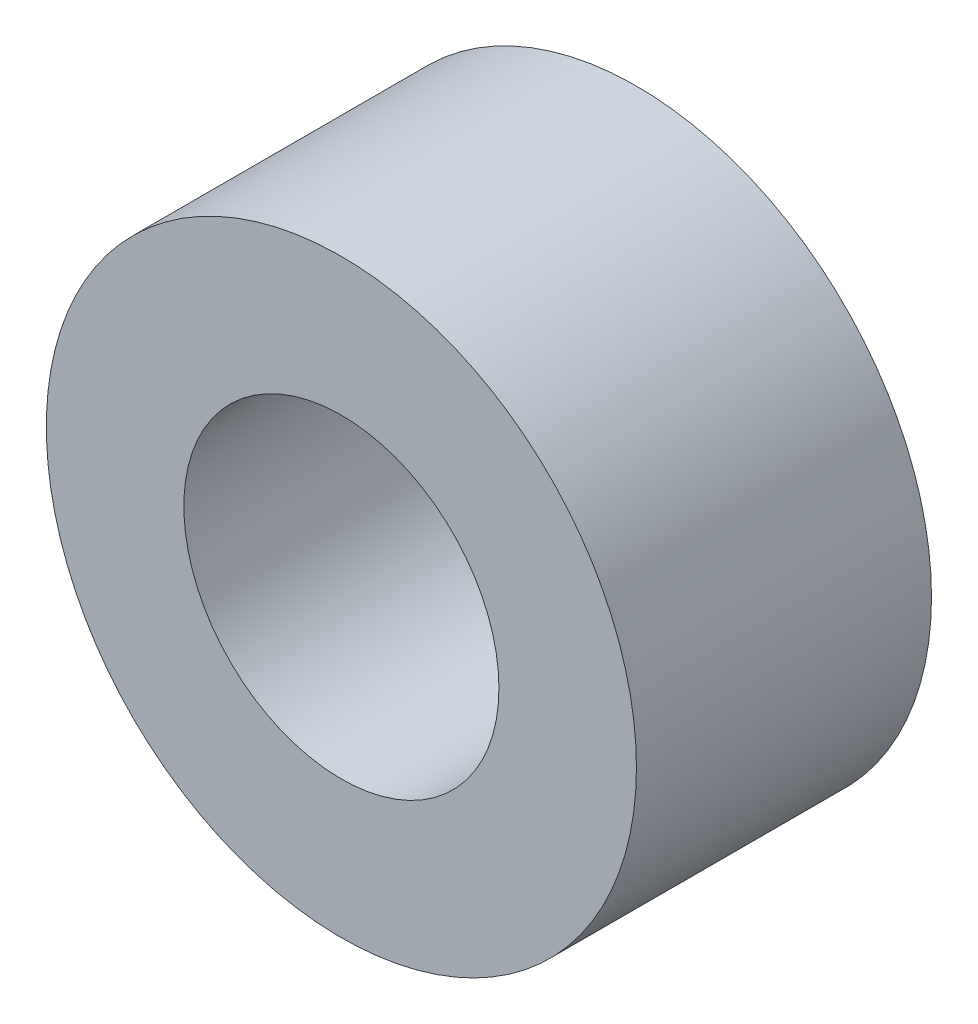
SolidWorks part; units mm, degrees
material "Custom Plastic"
ref_plane "X-Y Datum" through (0, 0, 0) normal (0, 0, 1) x (1, 0, 0)
ref_plane "X-Z Datum" through (0, 0, 0) normal (0, 1, 0) x (1, 0, 0)
ref_plane "Y-Z Datum" through (0, 0, 0) normal (1, 0, 0) x (0, 0, -1)
sketch "Sketch1" plane through (0, 0, 0) normal (0, 0, 1) x (1, 0, 0)
  circle A0 centre (0, 0) radius 3.1369 construction
  circle A1 centre (0, 0) radius 6.35
  circle A2 centre (0, 0) radius 3.3909
  dimension "D1" = 6.2738
  dimension "D2" = 12.7
  dimension "D3" = 0.254
extrude "Boss-Extrude1" add sketch "Sketch1" along normal blind 6.35
